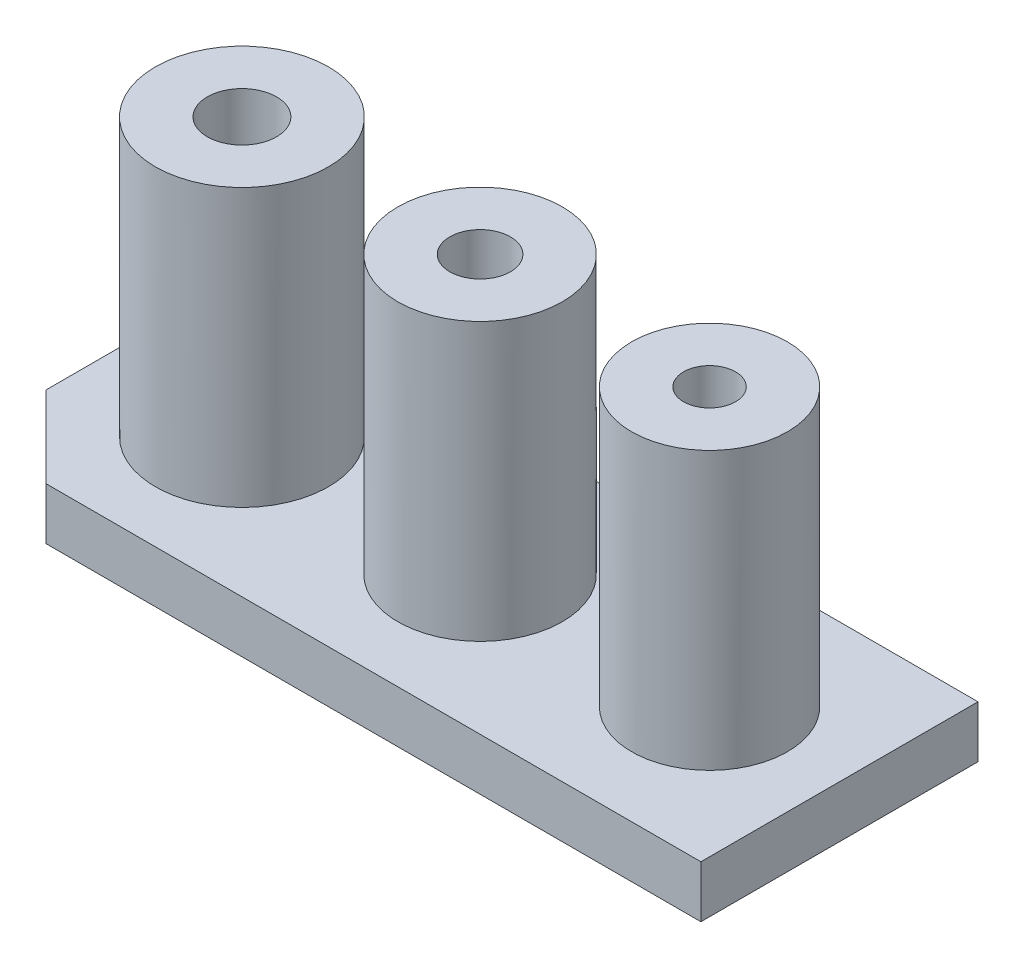
SolidWorks part; units mm, degrees
ref_plane "Front Plane" through (0, 0, 0) normal (0, 0, 1) x (1, 0, 0)
ref_plane "Top Plane" through (0, 0, 0) normal (0, 1, 0) x (1, 0, 0)
ref_plane "Right Plane" through (0, 0, 0) normal (1, 0, 0) x (0, 0, -1)
sketch "Sketch1" plane through (0, 0, 0) normal (0, 1, 0) x (1, 0, 0)
  line L0 (2.5, 0) -> (4.5, 0) construction
  line L1 (9.25, 0) -> (11.25, 0) construction
  line L2 (0, -1) -> (0, -2.5) construction
  line L3 (6.875, -0.875) -> (6.875, -2.375) construction
  line L4 (13.5, -0.75) -> (13.5, -2.25) construction
  circle A0 centre (0, 0) radius 1
  circle A1 centre (6.875, 0) radius 0.875
  circle A2 centre (13.5, 0) radius 0.75
  circle A3 centre (0, 0) radius 2.5
  circle A4 centre (6.875, 0) radius 2.375
  circle A5 centre (13.5, 0) radius 2.25
  dimension "D1" = 2
  dimension "D3" = 1.75
  dimension "D4" = 1.5
  dimension "D5" = 1.5
  dimension "D2" = 2
extrude "Boss-Extrude1" add sketch "Sketch1" along normal blind 8
sketch "Sketch2" plane through (0, 0, 0) normal (0, -1, 0) x (1, 0, 0)
  line L0 (-2.5, 0) -> (-4, 0) construction
  line L1 (-4, 4) -> (17.25, 4)
  line L2 (-4, 4) -> (-4, -4)
  line L3 (-4, -4) -> (17.25, -4)
  line L4 (17.25, 4) -> (17.25, -4)
  line L5 (0, 2.5) -> (0, 4) construction
  line L6 (0, -2.5) -> (0, -4) construction
  line L7 (17.25, 0) -> (15.75, 0) construction
  line L8 (-4, 1.6569) -> (-1.6569, 4)
  line L9 (-2.8284, 2.8284) -> (-1.7678, 1.7678) construction
  circle A0 centre (0, 0) radius 2.5 construction
  circle A1 centre (13.5, 0) radius 2.25 construction
  circle M5 centre (0, 0) radius 2.5
  circle M6 centre (0, 0) radius 1
  dimension "D1" = 1.5
  dimension "D2" = 45
extrude "Boss-Extrude2" add sketch "Sketch2" along normal blind 1.5 contours L8 L2 L3 L4 L1 M5 | M5 M6 | M6
